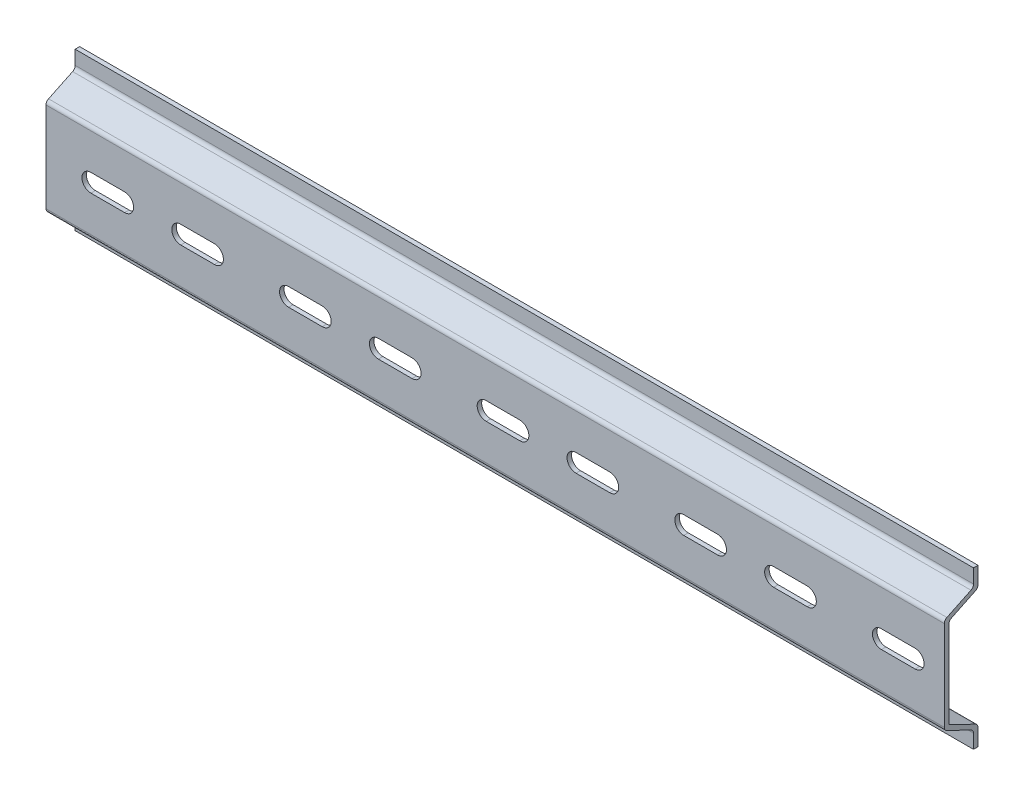
SolidWorks part; units mm, degrees
ref_plane "前视基准面" through (0, 0, 0) normal (0, 0, 1) x (1, 0, 0)
ref_plane "上视基准面" through (0, 0, 0) normal (0, 1, 0) x (1, 0, 0)
ref_plane "右视基准面" through (0, 0, 0) normal (1, 0, 0) x (0, 0, -1)
sketch "草图1" plane through (0, 0, 0) normal (1, 0, 0) x (0, 0, -1)
  line L0 (0, -10) -> (0, 10)
  line L1 (0, 10) -> (6.5, 13.1208)
  line L2 (6.5, 13.1208) -> (6.5, 17.5)
  line L3 (6.5, 17.5) -> (5.5, 17.5)
  line L4 (5.5, 17.5) -> (5.5, 13.75)
  line L5 (5.5, 13.75) -> (-1, 10.6292)
  line L6 (-1, 10.6292) -> (-1, -10.6292)
  line L7 (-14.3812, 0) -> (24.228, 0) construction
  line L8 (5.5, -13.75) -> (-1, -10.6292)
  line L9 (5.5, -17.5) -> (5.5, -13.75)
  line L10 (6.5, -17.5) -> (5.5, -17.5)
  line L11 (6.5, -13.1208) -> (6.5, -17.5)
  line L12 (0, -10) -> (6.5, -13.1208)
  point P12 (-1, 0)
  point P17 (0, 0)
  dimension "D1" = 7.5
  dimension "D2" = 1
  dimension "D3" = 1
  dimension "D4" = 1
  dimension "D5" = 27.5
  dimension "D6" = 35
  dimension "D7" = 20
extrude "凸台-拉伸1" add sketch "草图1" along normal blind 200
fillet "圆角1" radius 1 7 edges at (100, 13.75, -5.5) (100, 10.6292, 1) (100, 10, 0) (100, -10.6292, 1) (100, -13.1208, -6.5) (100, -13.75, -5.5) (100, 13.1208, -6.5)
sketch "草图2" plane through (0, 0, 0) normal (0, 0, -1) x (-1, 0, 0)
  line L0 (33.4315, 0) -> (-53.4315, 0) construction
  line L1 (-10, 0) -> (-17.5, 0) construction
  line L2 (-10, -2) -> (-17.5, -2)
  line L3 (-10, 2) -> (-17.5, 2)
  line L4 (-30, 0) -> (-37.5, 0) construction
  line L5 (-30, -2) -> (-37.5, -2)
  line L6 (-30, 2) -> (-37.5, 2)
  line L7 (-54, 0) -> (-61.5, 0) construction
  line L8 (-54, -2) -> (-61.5, -2)
  line L9 (-54, 2) -> (-61.5, 2)
  line L10 (-74, 0) -> (-81.5, 0) construction
  line L11 (-74, -2) -> (-81.5, -2)
  line L12 (-74, 2) -> (-81.5, 2)
  line L13 (-98, 0) -> (-105.5, 0) construction
  line L14 (-98, -2) -> (-105.5, -2)
  line L15 (-98, 2) -> (-105.5, 2)
  line L16 (-118, 0) -> (-125.5, 0) construction
  line L17 (-118, -2) -> (-125.5, -2)
  line L18 (-118, 2) -> (-125.5, 2)
  line L19 (-142, 0) -> (-149.5, 0) construction
  line L20 (-142, -2) -> (-149.5, -2)
  line L21 (-142, 2) -> (-149.5, 2)
  line L22 (-162, 0) -> (-169.5, 0) construction
  line L23 (-162, -2) -> (-169.5, -2)
  line L24 (-162, 2) -> (-169.5, 2)
  line L25 (-186, 0) -> (-193.5, 0) construction
  line L26 (-186, -2) -> (-193.5, -2)
  line L27 (-186, 2) -> (-193.5, 2)
  line L28 (-206, 0) -> (-213.5, 0) construction
  line L29 (-206, -2) -> (-213.5, -2)
  line L30 (-206, 2) -> (-213.5, 2)
  line L31 (-230, 0) -> (-237.5, 0) construction
  line L32 (-230, -2) -> (-237.5, -2)
  line L33 (-230, 2) -> (-237.5, 2)
  line L34 (-250, 0) -> (-257.5, 0) construction
  line L35 (-250, -2) -> (-257.5, -2)
  line L36 (-250, 2) -> (-257.5, 2)
  line L37 (-274, 0) -> (-281.5, 0) construction
  line L38 (-274, -2) -> (-281.5, -2)
  line L39 (-274, 2) -> (-281.5, 2)
  line L40 (-294, 0) -> (-301.5, 0) construction
  line L41 (-294, -2) -> (-301.5, -2)
  line L42 (-294, 2) -> (-301.5, 2)
  line L43 (-318, 0) -> (-325.5, 0) construction
  line L44 (-318, -2) -> (-325.5, -2)
  line L45 (-318, 2) -> (-325.5, 2)
  line L46 (-338, 0) -> (-345.5, 0) construction
  line L47 (-338, -2) -> (-345.5, -2)
  line L48 (-338, 2) -> (-345.5, 2)
  line L49 (-362, 0) -> (-369.5, 0) construction
  line L50 (-362, -2) -> (-369.5, -2)
  line L51 (-362, 2) -> (-369.5, 2)
  line L52 (-382, 0) -> (-389.5, 0) construction
  line L53 (-382, -2) -> (-389.5, -2)
  line L54 (-382, 2) -> (-389.5, 2)
  arc A0 (-10, -2) -> (-10, 2) centre (-10, 0) ccw
  arc A1 (-17.5, 2) -> (-17.5, -2) centre (-17.5, 0) ccw
  arc A2 (-30, -2) -> (-30, 2) centre (-30, 0) ccw
  arc A3 (-37.5, 2) -> (-37.5, -2) centre (-37.5, 0) ccw
  arc A4 (-54, -2) -> (-54, 2) centre (-54, 0) ccw
  arc A5 (-61.5, 2) -> (-61.5, -2) centre (-61.5, 0) ccw
  arc A6 (-74, -2) -> (-74, 2) centre (-74, 0) ccw
  arc A7 (-81.5, 2) -> (-81.5, -2) centre (-81.5, 0) ccw
  arc A8 (-98, -2) -> (-98, 2) centre (-98, 0) ccw
  arc A9 (-105.5, 2) -> (-105.5, -2) centre (-105.5, 0) ccw
  arc A10 (-118, -2) -> (-118, 2) centre (-118, 0) ccw
  arc A11 (-125.5, 2) -> (-125.5, -2) centre (-125.5, 0) ccw
  arc A12 (-142, -2) -> (-142, 2) centre (-142, 0) ccw
  arc A13 (-149.5, 2) -> (-149.5, -2) centre (-149.5, 0) ccw
  arc A14 (-162, -2) -> (-162, 2) centre (-162, 0) ccw
  arc A15 (-169.5, 2) -> (-169.5, -2) centre (-169.5, 0) ccw
  arc A16 (-186, -2) -> (-186, 2) centre (-186, 0) ccw
  arc A17 (-193.5, 2) -> (-193.5, -2) centre (-193.5, 0) ccw
  arc A18 (-206, -2) -> (-206, 2) centre (-206, 0) ccw
  arc A19 (-213.5, 2) -> (-213.5, -2) centre (-213.5, 0) ccw
  arc A20 (-230, -2) -> (-230, 2) centre (-230, 0) ccw
  arc A21 (-237.5, 2) -> (-237.5, -2) centre (-237.5, 0) ccw
  arc A22 (-250, -2) -> (-250, 2) centre (-250, 0) ccw
  arc A23 (-257.5, 2) -> (-257.5, -2) centre (-257.5, 0) ccw
  arc A24 (-274, -2) -> (-274, 2) centre (-274, 0) ccw
  arc A25 (-281.5, 2) -> (-281.5, -2) centre (-281.5, 0) ccw
  arc A26 (-294, -2) -> (-294, 2) centre (-294, 0) ccw
  arc A27 (-301.5, 2) -> (-301.5, -2) centre (-301.5, 0) ccw
  arc A28 (-318, -2) -> (-318, 2) centre (-318, 0) ccw
  arc A29 (-325.5, 2) -> (-325.5, -2) centre (-325.5, 0) ccw
  arc A30 (-338, -2) -> (-338, 2) centre (-338, 0) ccw
  arc A31 (-345.5, 2) -> (-345.5, -2) centre (-345.5, 0) ccw
  arc A32 (-362, -2) -> (-362, 2) centre (-362, 0) ccw
  arc A33 (-369.5, 2) -> (-369.5, -2) centre (-369.5, 0) ccw
  arc A34 (-382, -2) -> (-382, 2) centre (-382, 0) ccw
  arc A35 (-389.5, 2) -> (-389.5, -2) centre (-389.5, 0) ccw
  point P5 (-13.75, 0)
  point P14 (-33.75, 0)
  point P21 (-57.75, 0)
  point P28 (-77.75, 0)
  point P35 (-101.75, 0)
  point P42 (-121.75, 0)
  point P49 (-145.75, 0)
  point P56 (-165.75, 0)
  point P63 (-189.75, 0)
  point P70 (-209.75, 0)
  point P77 (-233.75, 0)
  point P84 (-253.75, 0)
  point P91 (-277.75, 0)
  point P98 (-297.75, 0)
  point P105 (-321.75, 0)
  point P112 (-341.75, 0)
  point P119 (-365.75, 0)
  point P126 (-385.75, 0)
  dimension "D1" = 2
  dimension "D2" = 7.5
  dimension "D3" = 10
  dimension "D4" = 2
  dimension "D5" = 9
extrude "切除-拉伸1" cut sketch "草图2" against normal blind 10
